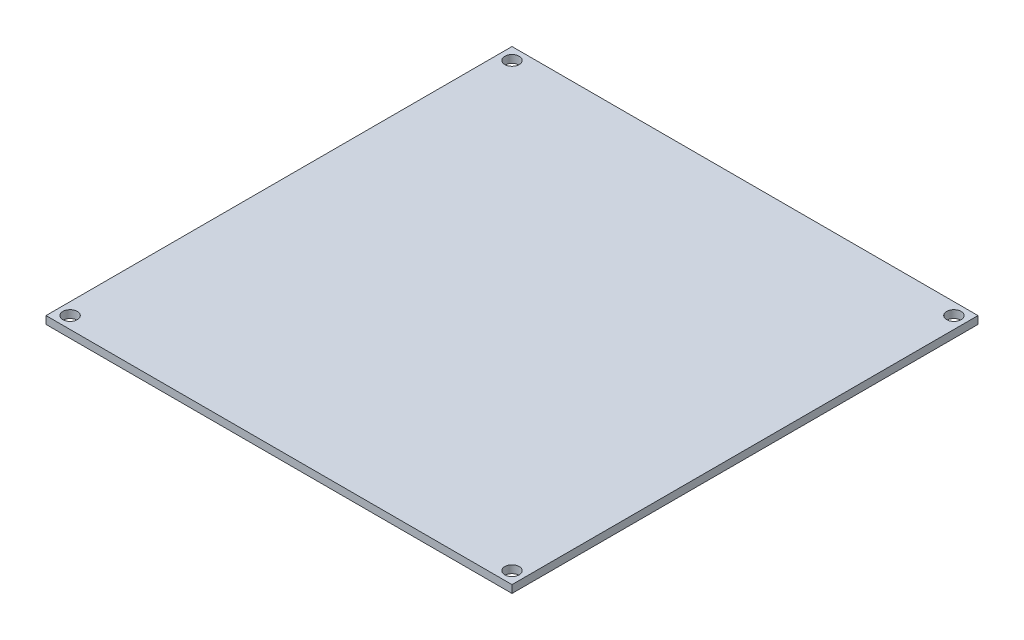
SolidWorks part; units mm, degrees
ref_plane "Front Plane" through (0, 0, 0) normal (0, 0, 1) x (1, 0, 0)
ref_plane "Top Plane" through (0, 0, 0) normal (0, 1, 0) x (1, 0, 0)
ref_plane "Right Plane" through (0, 0, 0) normal (1, 0, 0) x (0, 0, -1)
sketch "Sketch1" plane through (0, 0, 0) normal (0, 1, 0) x (1, 0, 0)
  line L0 (-55, 0) -> (55, 0) construction
  line L1 (-48.4, -48.4) -> (48.4, -48.4)
  line L2 (-48.4, -48.4) -> (-48.4, 48.4)
  line L3 (-48.4, 48.4) -> (48.4, 48.4)
  line L4 (48.4, -48.4) -> (48.4, 48.4)
  line L5 (-48.4, -48.4) -> (48.4, 48.4) construction
  line L6 (-48.4, 48.4) -> (48.4, -48.4) construction
  line L7 (0, -55) -> (0, 55) construction
  circle A0 centre (-45.9, 45.9) radius 1.5
  circle A1 centre (-45.9, -45.9) radius 1.5
  circle A2 centre (45.9, -45.9) radius 1.5
  circle A3 centre (45.9, 45.9) radius 1.5
  point P0 (0, 0)
  dimension "D5" = 3
  dimension "D1" = 96.8
  dimension "D2" = 96.8
  dimension "D3" = 2.5
  dimension "D4" = 2.5
extrude "Boss-Extrude1" add sketch "Sketch1" along normal blind 1.6
